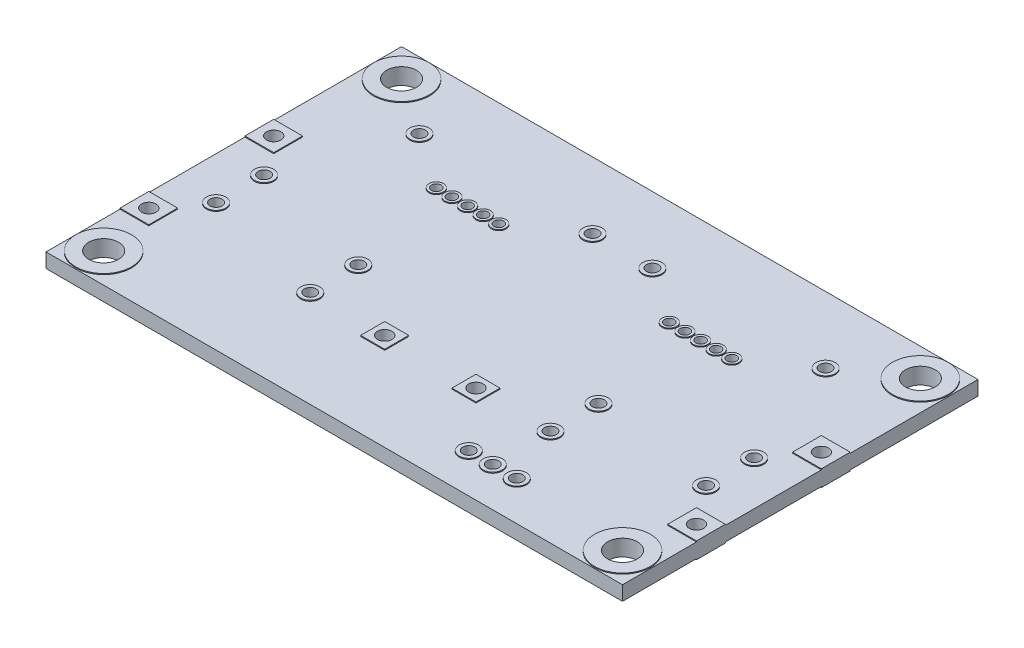
SolidWorks part; units mm, degrees
ref_plane "Front" through (0, 0, 0) normal (0, 0, 1) x (1, 0, 0)
ref_plane "Top" through (0, 0, 0) normal (0, 1, 0) x (1, 0, 0)
ref_plane "Right" through (0, 0, 0) normal (1, 0, 0) x (0, 0, -1)
sketch "Sketch1" plane through (0, 0, 0) normal (0, 1, 0) x (1, 0, 0)
  line L0 (-30, -18.5) -> (30, 18.5) construction
  line L1 (-30, 18.5) -> (30, 18.5)
  line L2 (-30, 18.5) -> (-30, -18.5)
  line L3 (-30, -18.5) -> (30, -18.5)
  line L4 (30, 18.5) -> (30, -18.5)
  point P4 (0, 0)
  dimension "D1" = 60
  dimension "D2" = 37
extrude "Boss-Extrude1" add sketch "Sketch1" along normal mid plane 1.5
sketch "Sketch2" plane through (0, -0.75, 0) normal (0, -1, 0) x (1, 0, 0)
  line L0 (0, 0) -> (0, 15.0269) construction
  line L1 (0, 0) -> (26, 0) construction
  line L2 (30, -18.5) -> (-30, -18.5) construction
  line L3 (15.375, -7.5) -> (8.875, -7.5) construction
  line L4 (12.125, -7.5) -> (12.125, -13.0911) construction
  line L6 (10.5, -7.5) -> (10.5, -9.9578) construction
  line L7 (-15.375, -7.5) -> (-8.875, -7.5) construction
  line L8 (-30, -18.5) -> (-30, 18.5) construction
  line L9 (-24.3532, 2.8) -> (-29.5979, 2.8) construction
  line L10 (-30, 18.5) -> (30, 18.5) construction
  line L11 (4.75, 8.5) -> (-4.75, 8.5) construction
  line L12 (10, 14.5) -> (15, 14.5) construction
  line L13 (30, 18.5) -> (30, -18.5) construction
  circle A0 centre (-27, 15.5) radius 1.55
  circle A1 centre (-27, -15.5) radius 1.55
  circle A2 centre (27, 15.5) radius 1.55
  circle A3 centre (27, -15.5) radius 1.55
  circle A4 centre (21.1375, -11.5) radius 0.625
  circle A5 centre (3.1125, -11.5) radius 0.625
  circle A6 centre (-3.1125, -11.5) radius 0.625
  circle A7 centre (-21.1375, -11.5) radius 0.625
  circle A8 centre (15.375, -7.5) radius 0.5
  circle A9 centre (8.875, -7.5) radius 0.5
  circle A10 centre (12.125, -7.5) radius 0.5
  circle A11 centre (10.5, -7.5) radius 0.5
  circle A12 centre (13.75, -7.5) radius 0.5
  circle A13 centre (-13.75, -7.5) radius 0.5
  circle A14 centre (-10.5, -7.5) radius 0.5
  circle A15 centre (-12.125, -7.5) radius 0.5
  circle A16 centre (-8.875, -7.5) radius 0.5
  circle A17 centre (-15.375, -7.5) radius 0.5
  circle A18 centre (-28.5, -3.7) radius 0.75
  circle A19 centre (-28.5, 9.3) radius 0.75
  circle A20 centre (28.5, 9.3) radius 0.75
  circle A21 centre (28.5, -3.7) radius 0.75
  circle A22 centre (-25.5, 0.3) radius 0.625
  circle A23 centre (-25.5, 5.3) radius 0.625
  circle A24 centre (25.5, 5.3) radius 0.625
  circle A25 centre (25.5, 0.3) radius 0.625
  circle A26 centre (-12.5, 8.5) radius 0.625
  circle A27 centre (-12.5, 3.5) radius 0.625
  circle A28 centre (12.5, 8.5) radius 0.625
  circle A29 centre (12.5, 3.5) radius 0.625
  circle A30 centre (4.75, 8.5) radius 0.75
  circle A31 centre (-4.75, 8.5) radius 0.75
  circle A32 centre (15, 14.5) radius 0.625
  circle A33 centre (12.5, 14.5) radius 0.625
  circle A34 centre (10, 14.5) radius 0.625
  dimension "D1" = 3.1
  dimension "D5" = 1.25
  dimension "D8" = 1
  dimension "D12" = 1.5
  dimension "D15" = 1.25
  dimension "D21" = 1.5
  dimension "D27" = 1.25
  dimension "D2" = 54
  dimension "D3" = 31
  dimension "D4" = 18.025
  dimension "D6" = 6.225
  dimension "D7" = 7
  dimension "D9" = 11
  dimension "D10" = 6.5
  dimension "D11" = 1.5
  dimension "D13" = 13
  dimension "D14" = 14.8
  dimension "D16" = 5
  dimension "D17" = 4.5
  dimension "D18" = 5
  dimension "D19" = 25
  dimension "D20" = 10
  dimension "D22" = 10
  dimension "D23" = 9.5
  dimension "D24" = 5
  dimension "D26" = 4
  dimension "D25" = 15
extrude "Cut-Extrude1" cut sketch "Sketch2" against normal up to next (1.5 mm away)
sketch "Sketch3" plane through (0, -0.75, 0) normal (0, -1, 0) x (1, 0, 0)
  line L0 (0, 0) -> (0, -13.8344) construction
  line L1 (30, 18.5) -> (30, -18.5) construction
  line L2 (30, -5.2) -> (27, -5.2)
  line L3 (30, -5.2) -> (30, -2.2)
  line L4 (30, -2.2) -> (27, -2.2)
  line L5 (27, -5.2) -> (27, -2.2)
  line L6 (30, -2.2) -> (27, -5.2) construction
  line L7 (30, 2.8) -> (20.2347, 2.8) construction
  line L8 (30, 10.8) -> (30, 7.8)
  line L9 (30, 10.8) -> (27, 10.8)
  line L10 (27, 10.8) -> (27, 7.8)
  line L11 (30, 7.8) -> (27, 7.8)
  line L12 (-30, 10.8) -> (-27, 10.8)
  line L13 (-30, 10.8) -> (-30, 7.8)
  line L14 (-30, 7.8) -> (-27, 7.8)
  line L15 (-27, 10.8) -> (-27, 7.8)
  line L16 (-30, -5.2) -> (-27, -5.2)
  line L17 (-30, -5.2) -> (-30, -2.2)
  line L18 (-30, -2.2) -> (-27, -2.2)
  line L19 (-27, -5.2) -> (-27, -2.2)
  line L20 (6, 9.75) -> (3.5, 7.25) construction
  line L21 (6, 7.25) -> (3.5, 7.25)
  line L22 (6, 7.25) -> (6, 9.75)
  line L23 (6, 9.75) -> (3.5, 9.75)
  line L24 (3.5, 7.25) -> (3.5, 9.75)
  line L25 (-6, 7.25) -> (-6, 9.75)
  line L26 (-6, 7.25) -> (-3.5, 7.25)
  line L27 (-3.5, 7.25) -> (-3.5, 9.75)
  line L28 (-6, 9.75) -> (-3.5, 9.75)
  circle A0 centre (27, 15.5) radius 2.9
  circle A1 centre (27, -15.5) radius 2.9
  circle A2 centre (-27, 15.5) radius 2.9
  circle A3 centre (-27, -15.5) radius 2.9
  circle A4 centre (15.375, -7.5) radius 0.75
  circle A5 centre (13.75, -7.5) radius 0.75
  circle A6 centre (12.125, -7.5) radius 0.75
  circle A7 centre (10.5, -7.5) radius 0.75
  circle A8 centre (8.875, -7.5) radius 0.75
  circle A9 centre (-8.875, -7.5) radius 0.75
  circle A10 centre (-10.5, -7.5) radius 0.75
  circle A11 centre (-12.125, -7.5) radius 0.75
  circle A12 centre (-28.5, 9.3) radius 0.75
  circle A13 centre (-13.75, -7.5) radius 0.75
  circle A14 centre (27, 15.5) radius 1.55 construction
  circle A15 centre (27, 15.5) radius 1.55
  circle A16 centre (-28.5, -3.7) radius 0.75
  circle A17 centre (-15.375, -7.5) radius 0.75
  circle A18 centre (25.5, 0.3) radius 0.625 construction
  circle A19 centre (15.375, -7.5) radius 0.5 construction
  circle A20 centre (25.5, 0.3) radius 0.625
  circle A21 centre (15.375, -7.5) radius 0.5
  circle A22 centre (25.5, 5.3) radius 0.625 construction
  circle A23 centre (13.75, -7.5) radius 0.5 construction
  circle A24 centre (27, -15.5) radius 1.55 construction
  circle A25 centre (27, -15.5) radius 1.55
  circle A26 centre (25.5, 5.3) radius 0.625
  circle A27 centre (13.75, -7.5) radius 0.5
  circle A28 centre (25.5, 0.3) radius 1
  circle A29 centre (12.125, -7.5) radius 0.5 construction
  circle A30 centre (-27, -15.5) radius 1.55 construction
  circle A31 centre (-27, -15.5) radius 1.55
  circle A32 centre (-27, 15.5) radius 1.55 construction
  circle A33 centre (-27, 15.5) radius 1.55
  circle A34 centre (25.5, 5.3) radius 1
  circle A35 centre (12.125, -7.5) radius 0.5
  circle A36 centre (10.5, -7.5) radius 0.5 construction
  circle A37 centre (10.5, -7.5) radius 0.5
  circle A38 centre (8.875, -7.5) radius 0.5 construction
  circle A39 centre (8.875, -7.5) radius 0.5
  circle A40 centre (-8.875, -7.5) radius 0.5 construction
  circle A41 centre (-8.875, -7.5) radius 0.5
  circle A42 centre (-10.5, -7.5) radius 0.5 construction
  circle A43 centre (-10.5, -7.5) radius 0.5
  circle A44 centre (-12.125, -7.5) radius 0.5 construction
  circle A45 centre (-12.125, -7.5) radius 0.5
  circle A46 centre (-13.75, -7.5) radius 0.5 construction
  circle A47 centre (-13.75, -7.5) radius 0.5
  circle A48 centre (-15.375, -7.5) radius 0.5 construction
  circle A49 centre (-15.375, -7.5) radius 0.5
  circle A50 centre (21.1375, -11.5) radius 0.625 construction
  circle A51 centre (21.1375, -11.5) radius 0.625
  circle A52 centre (3.1125, -11.5) radius 0.625 construction
  circle A53 centre (3.1125, -11.5) radius 0.625
  circle A54 centre (21.1375, -11.5) radius 1
  circle A55 centre (3.1125, -11.5) radius 1
  circle A56 centre (-3.1125, -11.5) radius 1
  circle A57 centre (-21.1375, -11.5) radius 1
  circle A58 centre (-3.1125, -11.5) radius 0.625
  circle A59 centre (-21.1375, -11.5) radius 0.625
  circle A60 centre (28.5, -3.7) radius 0.75 construction
  circle A61 centre (28.5, -3.7) radius 0.75
  circle A62 centre (28.5, 9.3) radius 0.75 construction
  circle A63 centre (28.5, 9.3) radius 0.75
  circle A64 centre (-25.5, 5.3) radius 0.625
  circle A65 centre (-25.5, 5.3) radius 1
  circle A66 centre (-25.5, 0.3) radius 1
  circle A67 centre (-25.5, 0.3) radius 0.625
  circle A68 centre (4.75, 8.5) radius 0.75 construction
  circle A69 centre (4.75, 8.5) radius 0.75
  circle A70 centre (12.5, 3.5) radius 0.625 construction
  circle A71 centre (12.5, 3.5) radius 0.625
  circle A72 centre (12.5, 8.5) radius 0.625 construction
  circle A73 centre (12.5, 8.5) radius 0.625
  circle A74 centre (12.5, 3.5) radius 1
  circle A75 centre (12.5, 8.5) radius 1
  circle A76 centre (-4.75, 8.5) radius 0.75
  circle A77 centre (-12.5, 8.5) radius 1
  circle A78 centre (-12.5, 8.5) radius 0.625
  circle A79 centre (-12.5, 3.5) radius 0.625
  circle A80 centre (-12.5, 3.5) radius 1
  circle A81 centre (15, 14.5) radius 0.625 construction
  circle A82 centre (15, 14.5) radius 0.625
  circle A83 centre (12.5, 14.5) radius 0.625 construction
  circle A84 centre (12.5, 14.5) radius 0.625
  circle A85 centre (10, 14.5) radius 0.625 construction
  circle A86 centre (10, 14.5) radius 0.625
  circle A87 centre (15, 14.5) radius 1
  circle A88 centre (12.5, 14.5) radius 1
  circle A89 centre (10, 14.5) radius 1
  dimension "D1" = 5.8
  dimension "D2" = 1.5
  dimension "D3" = 2
  dimension "D5" = 2
  dimension "D7" = 2
  dimension "D4" = 45
  dimension "D6" = 2.5
extrude "Boss-Extrude2" add sketch "Sketch3" along normal blind 0.1
mirror "Mirror1" about plane through (0, 0, 0) normal (0, 1, 0) of "Boss-Extrude2"
equation "\"D6@Sketch2\"=23-16.775"
